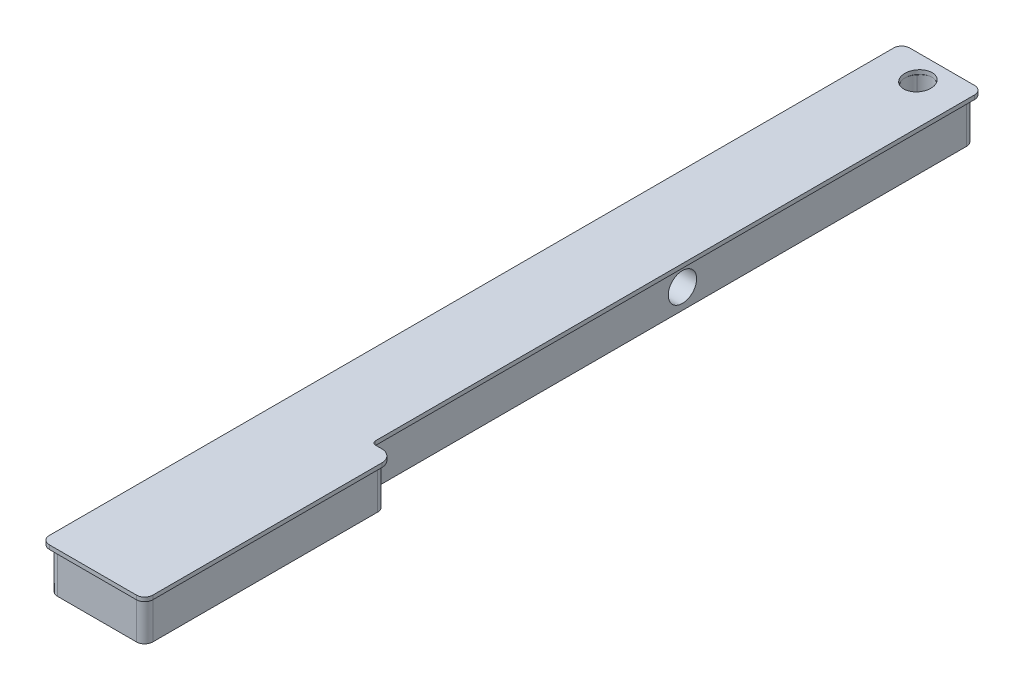
SolidWorks part; units mm, degrees
ref_plane "Plan de face" through (0, 0, 0) normal (0, 0, 1) x (1, 0, 0)
ref_plane "Plan de dessus" through (0, 0, 0) normal (0, 1, 0) x (1, 0, 0)
ref_plane "Plan de droite" through (0, 0, 0) normal (1, 0, 0) x (0, 0, -1)
sketch "Esquisse1" plane through (0, 0, 0) normal (0, 1, 0) x (1, 0, 0)
  line L0 (-11.3462, 33) -> (-11.3462, -105)
  line L1 (-11.3462, -105) -> (12.1338, -105)
  line L2 (6.636, 33) -> (6.636, -45.0033)
  line L3 (6.636, -45.0033) -> (6.636, -45.5659)
  line L4 (6.636, -45.5659) -> (12.1338, -45.5659)
  line L5 (12.1338, -45.5659) -> (12.1338, -105)
  line L6 (-11.3462, 33) -> (-11.3462, 105)
  line L7 (-11.3462, 105) -> (6.636, 105)
  line L8 (6.636, 105) -> (6.636, 33)
extrude "Boss.-Extru.1" add sketch "Esquisse1" along normal blind 10
sketch "Esquisse2" plane through (6.636, 0, 0) normal (1, 0, 0) x (0, 0, -1)
  line L0 (105, 5) -> (33, 5) construction
  line L1 (105, 10) -> (105, 0) construction
  circle A0 centre (33, 5) radius 3.5
extrude "Enlèv. mat.-Extru.1" cut sketch "Esquisse2" against normal blind 74 contours A0
sketch "Esquisse3" plane through (0, 10, 0) normal (0, 1, 0) x (1, 0, 0)
  line L0 (-2.3551, 105) -> (-2.3551, 100) construction
  line L1 (6.636, 105) -> (-11.3462, 105) construction
  line L2 (-11.3462, 105) -> (-11.3462, -105) construction
  ellipse E0 centre (-2.3519, 100) end of major axis (-2.3519, 103.5) minor radius 3
  dimension "D1" = 8.9944
  dimension "D2" = 5
extrude "Enlèv. mat.-Extru.2" cut sketch "Esquisse3" against normal blind 10
sketch "Esquisse4" plane through (0, 10, 0) normal (0, 1, 0) x (1, 0, 0)
  circle A0 centre (-2.3519, 100) radius 3.2
extrude "Enlèv. mat.-Extru.3" cut sketch "Esquisse4" against normal blind 10
fillet "Congé1" radius 2 6 edges at (6.636, 5, -105) (-11.3462, 5, -105) (6.636, 5, 45.5659) (12.1338, 5, 45.5659) (-11.3462, 5, 105) (12.1338, 5, 105)
sketch "Esquisse5" plane through (0, 10, 0) normal (0, 1, 0) x (1, 0, 0)
  line L0 (-10.7605, -104.4142) -> (-12.3462, -106) construction
  line L1 (-11.3462, 103) -> (-11.3462, -103) construction
  line L2 (-12.3462, -106) -> (13.1338, -106)
  line L3 (-12.3462, -106) -> (-12.3462, 106)
  line L4 (-12.3462, 106) -> (13.1338, 106)
  line L5 (13.1338, -106) -> (13.1338, 106)
  line L6 (12.1338, -103) -> (12.1338, -47.5659) construction
  line L7 (-9.3462, -105) -> (10.1338, -105) construction
  line L8 (4.636, 105) -> (-9.3462, 105) construction
  arc A0 (-11.3462, -103) -> (-9.3462, -105) centre (-9.3462, -103) ccw construction
  dimension "D1" = 1
  dimension "D2" = 1
  dimension "D3" = 1
  dimension "D4" = 1
extrude "Boss.-Extru.2" add sketch "Esquisse5" along normal blind 1
fillet "Congé2" radius 2 4 edges at (13.1338, 10.5, -106) (-12.3462, 10.5, -106) (-12.3462, 10.5, 106) (13.1338, 10.5, 106)
sketch "Esquisse6" plane through (0, 10, 0) normal (0, -1, 0) x (-1, 0, 0)
  line L0 (-7.2218, -44.9801) -> (-7.9289, -44.273) construction
  line L1 (-11.548, -46.1517) -> (-12.2551, -45.4445) construction
  line L2 (-12.1338, -48.8379) -> (-13.1338, -48.8379) construction
  line L3 (-12.1338, -103) -> (-12.1338, -47.5659) construction
  line L4 (-13.1338, -104) -> (-13.1338, 104) construction
  line L5 (-6.636, -43.5659) -> (-7.636, -43.5659) construction
  line L6 (-8.636, -45.5659) -> (-8.636, -44.5659) construction
  line L8 (-7.636, -43.5659) -> (-7.636, 107.1351)
  line L9 (-7.636, 107.1351) -> (-14.314, 107.1351)
  line L10 (-14.314, -43.5659) -> (-14.314, 107.1351)
  line L11 (-10.1338, -45.5659) -> (-10.1338, -44.5659) construction
  line L12 (-12.1338, -47.5659) -> (-13.1338, -47.5659) construction
  line L13 (-8.636, -44.5659) -> (-10.1338, -44.5659)
  line L14 (-13.1338, -47.5659) -> (-14.314, -43.5659)
  arc A0 (-8.636, -45.5659) -> (-6.636, -43.5659) centre (-8.636, -43.5659) ccw construction
  arc A1 (-10.1338, -45.5659) -> (-12.1338, -47.5659) centre (-10.1338, -47.5659) ccw construction
  arc A2 (-8.636, -44.5659) -> (-7.636, -43.5659) centre (-8.636, -43.5659) ccw
  arc A3 (-10.1338, -45.5659) -> (-12.1338, -47.5659) centre (-10.1338, -47.5659) ccw construction
  arc A4 (-10.1338, -44.5659) -> (-13.1338, -47.5659) centre (-10.1338, -47.5659) ccw
extrude "Enlèv. mat.-Extru.4" cut sketch "Esquisse6" against normal blind 1.5
fillet "Congé3" radius 2 1 edges at (7.636, 10.5, -106)
sketch "Esquisse9" plane through (0, 0, 0) normal (0, -1, 0) x (1, 0, 0)
  circle A0 centre (-2.3519, -100) radius 3.2
extrude "Enlèv. mat.-Extru.7" cut sketch "Esquisse9" against normal blind 15 contours A0
sketch "Esquisse11" plane through (0, 10, 0) normal (0, -1, 0) x (-1, 0, 0)
  arc A0 (-0.0074, 102.1619) -> (-0.0074, 97.8381) centre (2.3519, 100) ccw construction
  ellipse E0 centre (2.3519, 100) end of major axis (2.3519, 96.5) minor radius 3.2
extrude "Enlèv. mat.-Extru.8" cut sketch "Esquisse11" against normal blind 15
